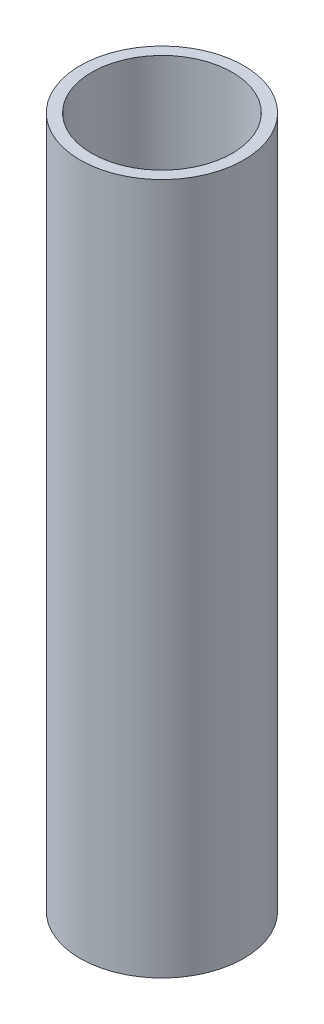
SolidWorks part; units mm, degrees
material "ABS"
ref_plane "Front Plane" through (0, 0, 0) normal (0, 0, 1) x (1, 0, 0)
ref_plane "Top Plane" through (0, 0, 0) normal (0, 1, 0) x (1, 0, 0)
ref_plane "Right Plane" through (0, 0, 0) normal (1, 0, 0) x (0, 0, -1)
sketch "Sketch1" plane through (0, 0, 0) normal (0, 1, 0) x (1, 0, 0)
  circle A0 centre (0, 0) radius 7.625
  circle A1 centre (0, 0) radius 8.875
  dimension "D1" = 17.75
  dimension "D2" = 15.25
extrude "Boss-Extrude1" add sketch "Sketch1" along normal blind 75
